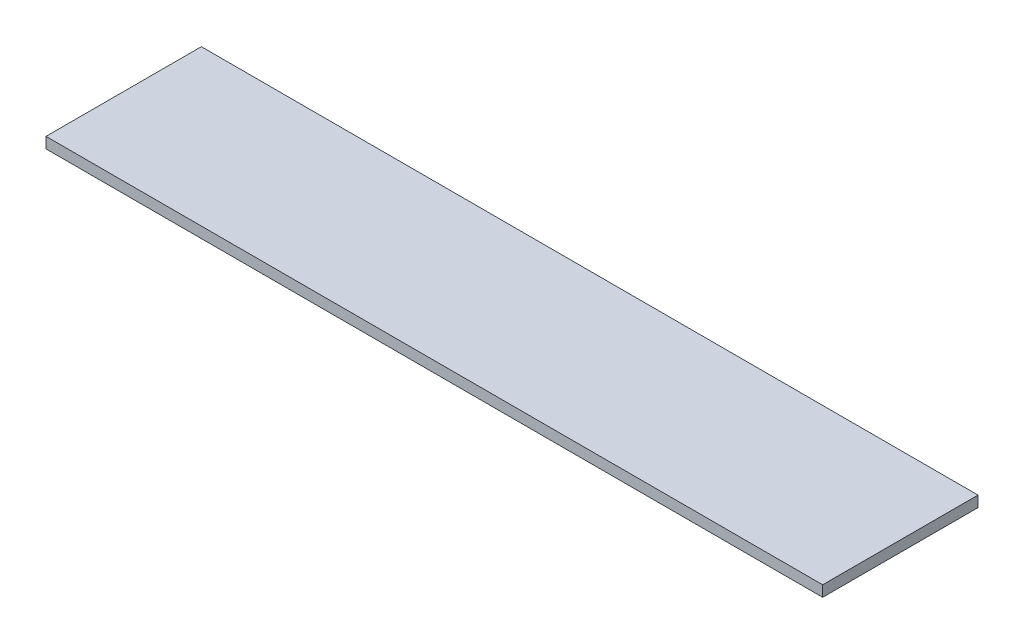
SolidWorks part; units mm, degrees
ref_plane "Front Plane" through (0, 0, 0) normal (0, 0, 1) x (1, 0, 0)
ref_plane "Top Plane" through (0, 0, 0) normal (0, 1, 0) x (1, 0, 0)
ref_plane "Right Plane" through (0, 0, 0) normal (1, 0, 0) x (0, 0, -1)
sketch "Sketch1" plane through (0, 0, 0) normal (0, 1, 0) x (1, 0, 0)
  line L1 (-25, -5) -> (25, -5)
  line L2 (-25, -5) -> (-25, 5)
  line L3 (-25, 5) -> (25, 5)
  line L4 (25, -5) -> (25, 5)
  line L5 (-25, -5) -> (25, 5) construction
  line L6 (-25, 5) -> (25, -5) construction
  point P0 (0, 0)
  dimension "D1" = 10
  dimension "D2" = 50
extrude "Boss-Extrude1" add sketch "Sketch1" along normal blind 0.7
